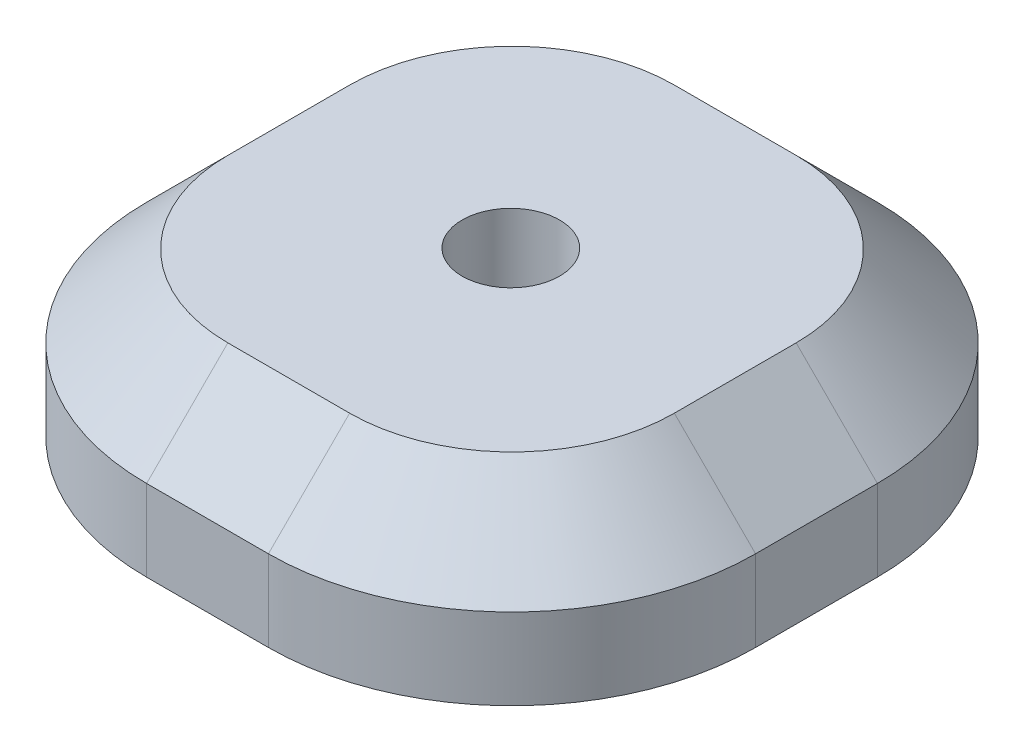
SolidWorks part; units mm, degrees
ref_plane "前基準面" through (0, 0, 0) normal (0, 0, 1) x (1, 0, 0)
ref_plane "上基準面" through (0, 0, 0) normal (0, 1, 0) x (1, 0, 0)
ref_plane "右基準面" through (0, 0, 0) normal (1, 0, 0) x (0, 0, -1)
sketch "草圖1" plane through (0, 0, 0) normal (0, 1, 0) x (1, 0, 0)
  line L1 (0, 0) -> (75, 0)
  line L2 (0, 0) -> (0, 75)
  line L3 (0, 75) -> (75, 75)
  line L4 (75, 0) -> (75, 75)
  dimension "D1" = 75
  dimension "D2" = 75
extrude "填料-伸長1" add sketch "草圖1" along normal blind 20
fillet "圓角1" radius 30 4 edges at (0, 10, -75) (75, 10, -75) (75, 10, 0) (0, 10, 0)
chamfer "導角1" distance 10 angle 45 8 edges at (0, 20, -37.5) (8.7868, 20, -8.7868) (8.7868, 20, -66.2132) (37.5, 20, 0) (37.5, 20, -75) (66.2132, 20, -8.7868) (66.2132, 20, -66.2132) (75, 20, -37.5)
sketch "草圖2" plane through (0, 0, 0) normal (0, -1, 0) x (1, 0, 0)
  line L0 (30, 0) -> (45, 0) construction
  line L1 (25, -25) -> (50, -25)
  line L2 (25, -25) -> (25, -50)
  line L3 (25, -50) -> (50, -50)
  line L4 (50, -25) -> (50, -50)
  line L5 (45, -75) -> (30, -75) construction
  line L6 (75, -30) -> (75, -45) construction
  line L7 (0, -45) -> (0, -30) construction
  dimension "D1" = 25
  dimension "D2" = 25
  dimension "D3" = 25
  dimension "D4" = 25
hole_wizard "Ø20.0mm 定位孔1" positions "3D草圖2" profile "草圖6" hole size "Ø20.0" standard "ISO"
sketch3d "3D草圖2"
  point P12 (25, 0, -25)
  point P15 (50, 0, -25)
  point P18 (50, 0, -50)
  point P25 (25, 0, -50)
sketch "草圖6" plane through (25, 0, -25) normal (1, 0, 0) x (0, 0, -1)
  line L0 (0, 0) -> (0, 13.6052)
  line L1 (0, 13.6052) -> (6, 10)
  line L2 (6, 10) -> (6, 0)
  line L5 (6, 0) -> (0, 0)
  line L10 (0, 13.6052) -> (-6, 10) construction
  line L11 (0, -6.35) -> (0, 107.95) construction
  dimension "鑽孔直徑" = 12
  dimension "鑽孔深度" = 10
  dimension "導頭角度" = 118
sketch "草圖9" plane through (0, 20, 0) normal (0, 1, 0) x (1, 0, 0)
  line L0 (65, 37.5) -> (10, 37.5)
  line L1 (65, 30) -> (65, 45) construction
  line L2 (10, 45) -> (10, 30) construction
  line L3 (37.5, 65) -> (37.5, 10)
  line L4 (45, 65) -> (30, 65) construction
  line L5 (30, 10) -> (45, 10) construction
  point P12 (37.5, 37.5)
hole_wizard "Ø20.0mm 定位孔2" positions "草圖12" profile "草圖13" hole size "Ø20.0" standard "ISO"
sketch "草圖12" plane through (0, 20, 0) normal (0, 1, 0) x (1, 0, 0)
  point P0 (37.318, 37.5396)
sketch "草圖13" plane through (37.318, 20, -37.5396) normal (1, 0, 0) x (0, 0, 1)
  line L0 (0, 0) -> (0, 13.6052)
  line L1 (0, 13.6052) -> (6, 10)
  line L2 (6, 10) -> (6, 0)
  line L5 (6, 0) -> (0, 0)
  line L10 (0, 13.6052) -> (-6, 10) construction
  line L11 (0, -6.35) -> (0, 107.95) construction
  dimension "鑽孔直徑" = 12
  dimension "鑽孔深度" = 10
  dimension "導頭角度" = 118
